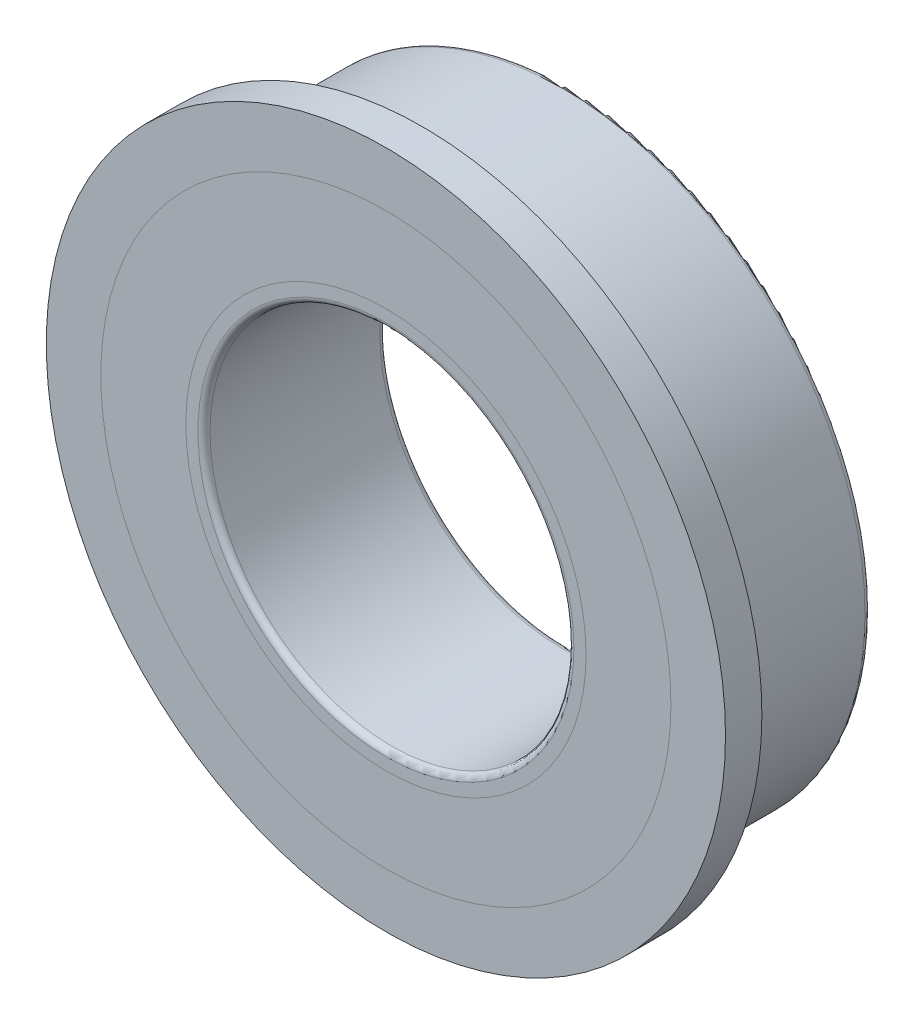
SolidWorks part; units mm, degrees
ref_plane "正面" through (0, 0, 0) normal (0, 0, 1) x (1, 0, 0)
ref_plane "平面" through (0, 0, 0) normal (0, 1, 0) x (1, 0, 0)
ref_plane "右側面" through (0, 0, 0) normal (1, 0, 0) x (0, 0, -1)
sketch "ｽｹｯﾁ1" plane through (0, 0, 0) normal (0, 0, 1) x (1, 0, 0)
  circle A0 centre (0, 0) radius 5
  circle A1 centre (0, 0) radius 3
  dimension "D1" = 6
  dimension "D2" = 10
extrude "ﾎﾞｽ - 押し出し1" add sketch "ｽｹｯﾁ1" along normal blind 3
sketch "ｽｹｯﾁ2" plane through (0, 0, 3) normal (0, 0, 1) x (1, 0, 0)
  circle A0 centre (0, 0) radius 5.6
  circle A1 centre (0, 0) radius 3 construction
  circle A2 centre (0, 0) radius 3
  dimension "D1" = 11.2
extrude "ﾎﾞｽ - 押し出し2" add sketch "ｽｹｯﾁ2" against normal blind 0.6
fillet "ﾌｨﾚｯﾄ1" radius 0.1 3 edges at (3, 0, 0) (5, 0, 0) (3, 0, 3)
sketch "ｽｹｯﾁ3" plane through (0, 0, 3) normal (0, 0, 1) x (1, 0, 0)
  line L0 (0, 3) -> (0, 5) construction
  line L1 (-3.9192, 4) -> (3.9192, 4) construction
  circle A0 centre (0, 0) radius 3 construction
  circle A1 centre (0, 0) radius 5 construction
  circle A2 centre (0, 0) radius 3.3
  circle A3 centre (0, 0) radius 4.7
  circle A4 centre (0, 0) radius 5.6 construction
  point P10 (0, 3.3)
  point P11 (0, 4.7)
  point P19 (0, 4)
  dimension "D1" = 6.6
split line "分割ﾗｲﾝ1"
